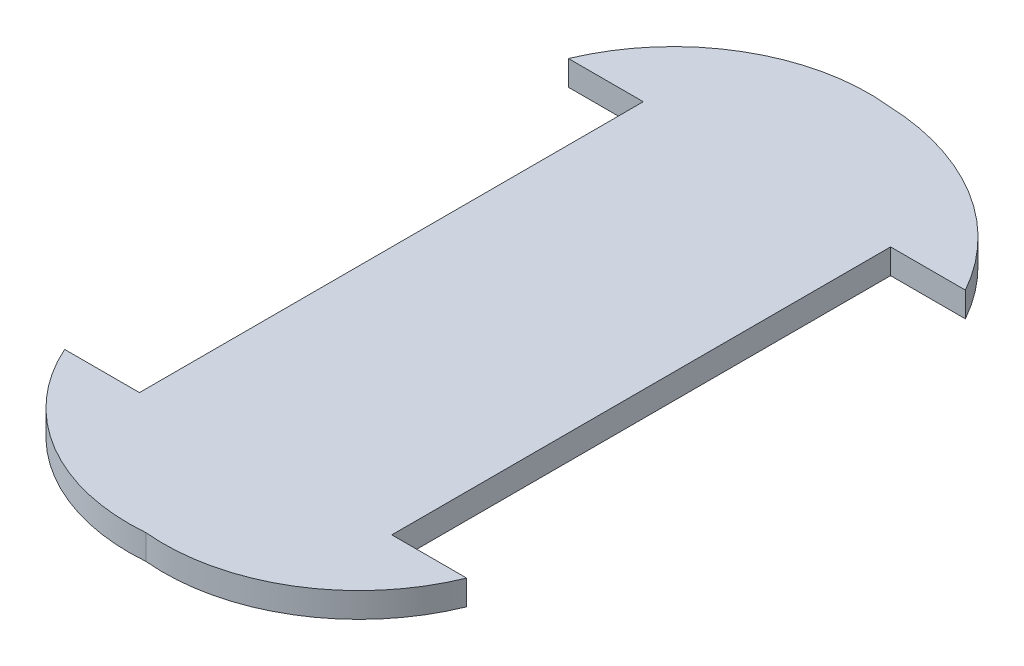
SolidWorks part; units mm, degrees
ref_plane "Front Plane" through (0, 0, 0) normal (0, 0, 1) x (1, 0, 0)
ref_plane "Top Plane" through (0, 0, 0) normal (0, 1, 0) x (1, 0, 0)
ref_plane "Right Plane" through (0, 0, 0) normal (1, 0, 0) x (0, 0, -1)
sketch "Sketch1" plane through (0, 0, 0) normal (0, 1, 0) x (1, 0, 0)
  line L0 (0, 100) -> (0, -100) construction
  line L1 (-50, 0) -> (50, 0) construction
  line L2 (50, 100) -> (50, -100)
  line L3 (50, -100) -> (80, -100)
  line L4 (50, 100) -> (80, 100)
  line L5 (-80, -101.1822) -> (-50, -101.1822)
  line L6 (-50, -101.1822) -> (-50, 100.8334)
  line L7 (-50, 100.8334) -> (-80, 100.8334)
  arc A0 (80, -100) -> (0, -148.53) centre (7.3809, -70.4936) cw
  arc A1 (-80, 100.8334) -> (0.7957, 148.5188) centre (-7.6831, 70.594) cw
  arc A2 (0, -148.53) -> (-80, -101.1822) centre (-6.5733, -68.3776) cw
  arc A3 (0.7957, 148.5188) -> (80, 100) centre (-2.7842, 53.7669) cw
  dimension "D6" = 30
  dimension "D1" = 100
  dimension "D2" = 50
  dimension "D3" = 200
  dimension "D4" = 100
  dimension "D5" = 30
  dimension "D7" = 48.5253
  dimension "D8" = 48.53
extrude "Boss-Extrude2" add sketch "Sketch1" along normal blind 10
